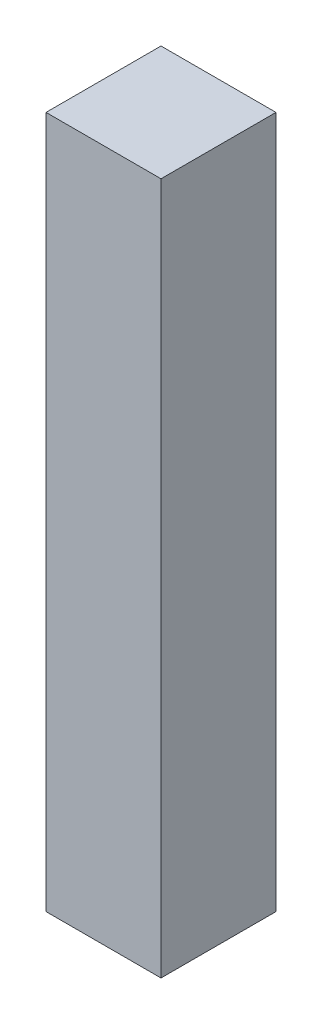
SolidWorks part; units mm, degrees
ref_plane "前视基准面" through (0, 0, 0) normal (0, 0, 1) x (1, 0, 0)
ref_plane "上视基准面" through (0, 0, 0) normal (0, 1, 0) x (1, 0, 0)
ref_plane "右视基准面" through (0, 0, 0) normal (1, 0, 0) x (0, 0, -1)
other "Configuration Table"
sketch "草图1" plane through (0, 0, 0) normal (0, 1, 0) x (1, 0, 0)
  line L1 (-10, 10) -> (10, 10)
  line L2 (-10, 10) -> (-10, -10)
  line L3 (-10, -10) -> (10, -10)
  line L4 (10, 10) -> (10, -10)
  line L5 (-10, 10) -> (10, -10) construction
  line L6 (-10, -10) -> (10, 10) construction
  point P0 (0, 0)
  dimension "D1" = 20
  dimension "D2" = 20
extrude "凸台-拉伸1" add sketch "草图1" along normal blind 120.4
